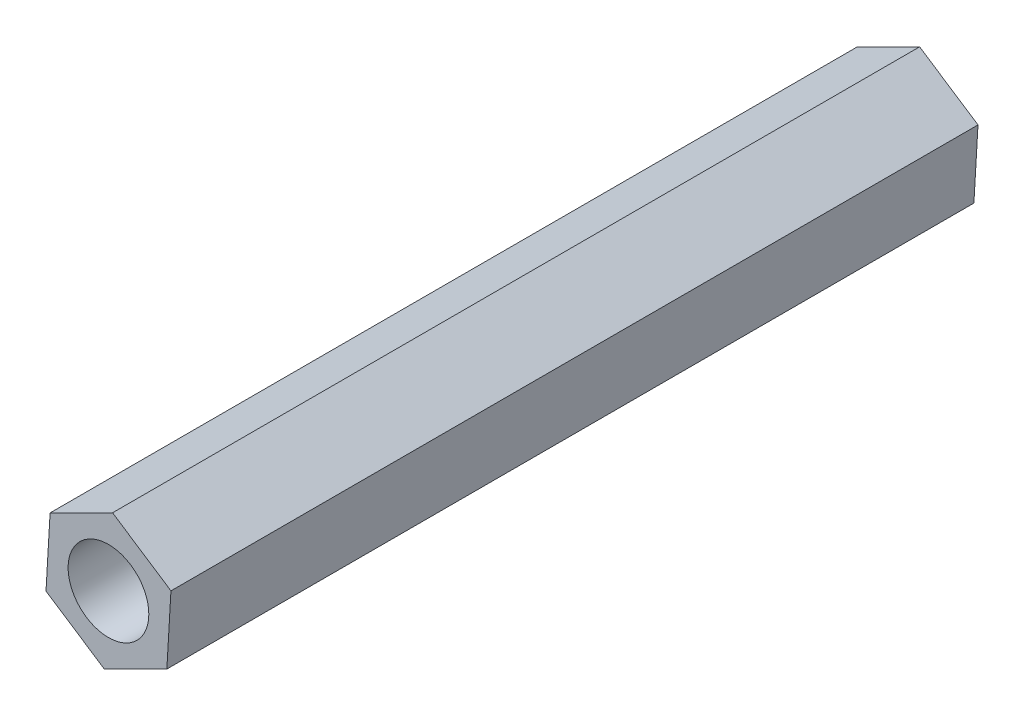
SolidWorks part; units mm, degrees
ref_plane "前视基准面" through (0, 0, 0) normal (0, 0, 1) x (1, 0, 0)
ref_plane "上视基准面" through (0, 0, 0) normal (0, 1, 0) x (1, 0, 0)
ref_plane "右视基准面" through (0, 0, 0) normal (1, 0, 0) x (0, 0, -1)
sketch "草图1" plane through (0, 0, 0) normal (0, 0, 1) x (1, 0, 0)
  line L1 (3.0964, 1.5531) -> (0.2032, 3.4581)
  line L2 (0.2032, 3.4581) -> (-2.8932, 1.905)
  line L3 (-2.8932, 1.905) -> (-3.0964, -1.5531)
  line L4 (-3.0964, -1.5531) -> (-0.2032, -3.4581)
  line L5 (-0.2032, -3.4581) -> (2.8932, -1.905)
  line L6 (2.8932, -1.905) -> (3.0964, 1.5531)
  circle A0 centre (0, 0) radius 3 construction
  circle A1 centre (0, 0) radius 2
extrude "凸台-拉伸1" add sketch "草图1" along normal blind 40
